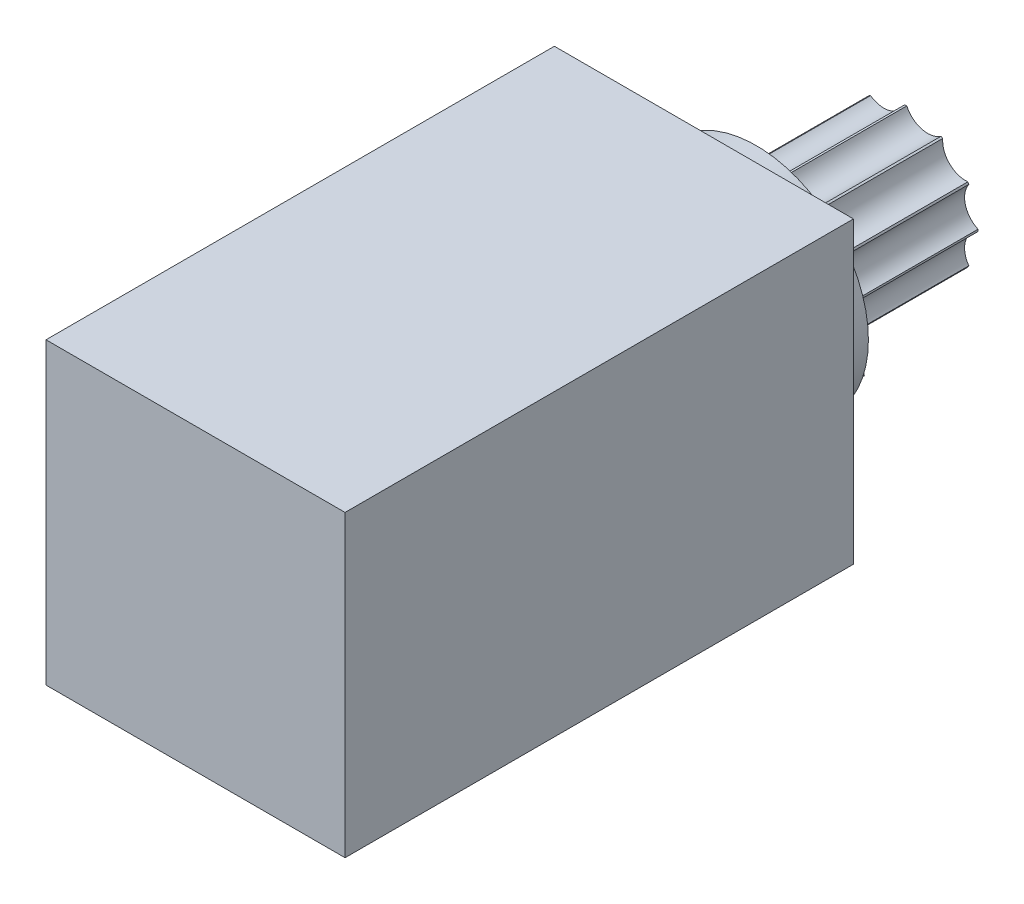
SolidWorks part; units mm, degrees
ref_plane "Alzado" through (0, 0, 0) normal (0, 0, 1) x (1, 0, 0)
ref_plane "Planta" through (0, 0, 0) normal (0, 1, 0) x (1, 0, 0)
ref_plane "Vista lateral" through (0, 0, 0) normal (1, 0, 0) x (0, 0, -1)
sketch "Croquis1" plane through (0, 0, 0) normal (0, 0, 1) x (1, 0, 0)
  circle A0 centre (0, 0) radius 10
extrude "Saliente-Extruir1" add sketch "Croquis1" along normal blind 20
sketch "Croquis2" plane through (0, 0, 0) normal (0, 0, -1) x (-1, 0, 0)
  line L0 (0.133, 9.6583) -> (-0.133, 9.6583)
  line L1 (-4.714, 8.4309) -> (-4.9444, 8.2979)
  line L2 (-8.2979, 4.9444) -> (-8.4309, 4.714)
  line L3 (-9.6583, 0.133) -> (-9.6583, -0.133)
  line L4 (-8.4309, -4.714) -> (-8.2979, -4.9444)
  line L5 (-4.9444, -8.2979) -> (-4.714, -8.4309)
  line L6 (-0.133, -9.6583) -> (0.133, -9.6583)
  line L7 (4.714, -8.4309) -> (4.9444, -8.2979)
  line L8 (8.2979, -4.9444) -> (8.4309, -4.714)
  line L9 (9.6583, 0.133) -> (9.6583, -0.133)
  line L10 (8.2979, 4.9444) -> (8.4309, 4.714)
  line L11 (4.714, 8.4309) -> (4.9444, 8.2979)
  circle A0 centre (0, 0) radius 10
  arc A1 (-4.714, 8.4309) -> (-0.133, 9.6583) centre (-2.9328, 10.9452) ccw
  arc A6 (8.4309, 4.714) -> (9.6583, 0.133) centre (10.9452, 2.9328) ccw
  arc A7 (9.6583, -0.133) -> (8.4309, -4.714) centre (10.9452, -2.9328) ccw
  arc A8 (8.2979, -4.9444) -> (4.9444, -8.2979) centre (8.0125, -8.0125) ccw
  arc A10 (-0.133, -9.6583) -> (-4.714, -8.4309) centre (-2.9328, -10.9452) ccw
  arc A11 (4.714, -8.4309) -> (0.133, -9.6583) centre (2.9328, -10.9452) ccw
  arc A13 (-8.4309, -4.714) -> (-9.6583, -0.133) centre (-10.9452, -2.9328) ccw
  arc A14 (-9.6583, 0.133) -> (-8.4309, 4.714) centre (-10.9452, 2.9328) ccw
  arc A15 (0.133, 9.6583) -> (4.714, 8.4309) centre (2.9328, 10.9452) ccw
  arc A18 (-8.2979, 4.9444) -> (-4.9444, 8.2979) centre (-8.0125, 8.0125) ccw
  arc A20 (-4.9444, -8.2979) -> (-8.2979, -4.9444) centre (-8.0125, -8.0125) ccw
  arc A26 (4.9444, 8.2979) -> (8.2979, 4.9444) centre (8.0125, 8.0125) ccw
extrude "Cortar-Extruir2" cut sketch "Croquis2" against normal blind 20
sketch "Croquis3" plane through (0, 0, 20) normal (0, 0, 1) x (1, 0, 0)
  circle A0 centre (0, 0) radius 15
extrude "Saliente-Extruir2" add sketch "Croquis3" along normal blind 5
sketch "Croquis4" plane through (0, 0, 20) normal (0, 0, -1) x (-1, 0, 0)
  line L0 (-4.9444, -8.2979) -> (-8.2979, -4.9444)
  line L1 (-6.6211, -6.6211) -> (-9.4495, -9.4495)
  line L2 (-9.4495, -9.4495) -> (-8.2979, -4.9444)
  line L3 (-4.9444, -8.2979) -> (-9.4495, -9.4495)
  circle A1 centre (-8.0125, -8.0125) radius 3.0813
  arc M15 (-4.9444, -8.2979) -> (-8.2979, -4.9444) centre (-8.0125, -8.0125) ccw
extrude "Saliente-Extruir3" add sketch "Croquis4" along normal blind 5 contours L2 L1 L0 | L3 L0 L1 | L0 M15
sketch "Croquis6" plane through (0, 0, 25) normal (0, 0, 1) x (1, 0, 0)
  line L1 (-20, -20) -> (20, -20)
  line L2 (-20, -20) -> (-20, 20)
  line L3 (-20, 20) -> (20, 20)
  line L4 (20, -20) -> (20, 20)
  line L5 (-20, -20) -> (20, 20) construction
  line L6 (-20, 20) -> (20, -20) construction
  point P0 (0, 0)
  dimension "D1" = 40
extrude "Saliente-Extruir4" add sketch "Croquis6" along normal blind 70
sketch "Croquis8" plane through (0, 0, 25) normal (0, 0, -1) x (-1, 0, 0)
  line L1 (-20, -20) -> (20, -20)
  line L2 (-20, -20) -> (-20, 20)
  line L3 (-20, 20) -> (20, 20)
  line L4 (20, -20) -> (20, 20)
  line L5 (-20, -20) -> (20, 20) construction
  line L6 (-20, 20) -> (20, -20) construction
  circle A0 centre (0, 0) radius 11.25
extrude "Cortar-Extruir3" cut sketch "Croquis8" against normal blind 2 contours L4 L3 L2 L1 | A0
